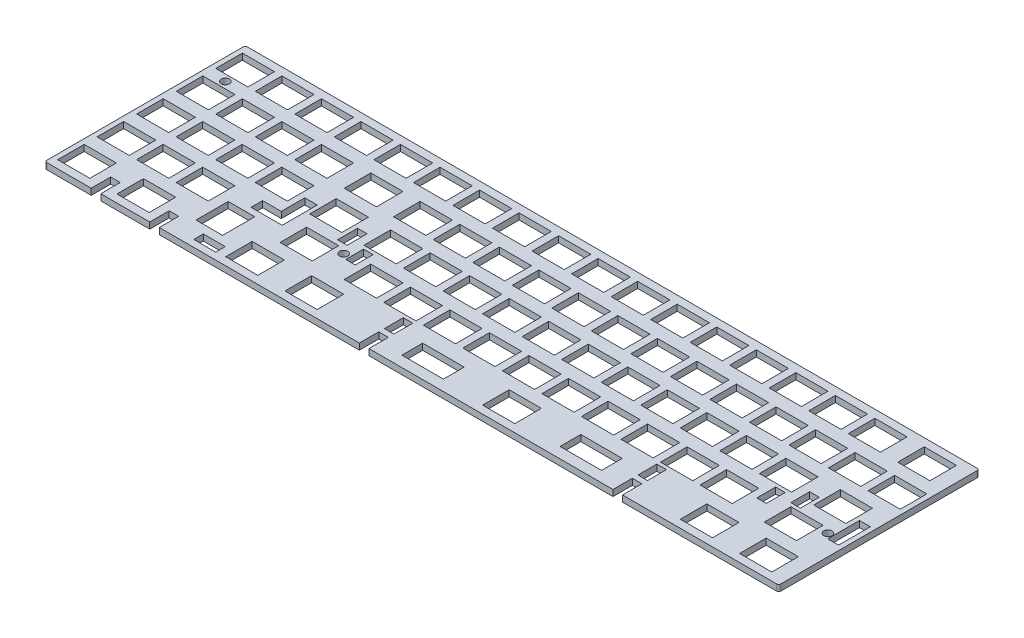
SolidWorks part; units mm, degrees
ref_plane "Front Plane" through (0, 0, 0) normal (0, 0, 1) x (1, 0, 0)
ref_plane "Top Plane" through (0, 0, 0) normal (0, 1, 0) x (1, 0, 0)
ref_plane "Right Plane" through (0, 0, 0) normal (1, 0, 0) x (0, 0, -1)
sketch "Sketch1" plane through (0, 0, 0) normal (0, 1, 0) x (1, 0, 0)
  line L0 (83.8437, 47.45) -> (83.8437, 30.525)
  line L1 (83.8437, 30.525) -> (68.8437, 30.525)
  line L2 (68.8437, 30.525) -> (68.8437, 36.125)
  line L3 (68.8437, 36.125) -> (77.8437, 36.125)
  line L4 (77.8437, 36.125) -> (77.8437, 47.45)
  line L5 (77.8437, 47.45) -> (83.8437, 47.45)
  line L6 (68.45, 7.925) -> (79.05, 7.925)
  line L7 (79.05, 7.925) -> (79.05, 3.325)
  line L8 (79.05, 3.325) -> (68.45, 3.325)
  line L9 (68.45, 3.325) -> (68.45, 7.925)
  line L10 (118.0062, 40.2) -> (113.4062, 40.2)
  line L11 (113.4062, 40.2) -> (113.4062, 31.6)
  line L12 (113.4062, 31.6) -> (118.0062, 31.6)
  line L13 (118.0062, 31.6) -> (118.0062, 40.2)
  line L14 (107.8437, 37.85) -> (107.8437, 47.45)
  line L15 (107.8437, 47.45) -> (103.2437, 47.45)
  line L16 (103.2437, 47.45) -> (103.2437, 37.85)
  line L17 (103.2437, 37.85) -> (107.8437, 37.85)
  line L18 (151.5875, 21.15) -> (156.1875, 21.15)
  line L19 (156.1875, 21.15) -> (156.1875, 12.05)
  line L20 (156.1875, 12.05) -> (151.5875, 12.05)
  line L21 (151.5875, 12.05) -> (151.5875, 21.15)
  line L22 (278.3875, 21.15) -> (273.7875, 21.15)
  line L23 (273.7875, 21.15) -> (273.7875, 12.05)
  line L24 (273.7875, 12.05) -> (278.3875, 12.05)
  line L25 (278.3875, 12.05) -> (278.3875, 21.15)
  line L26 (22.375, 0) -> (22.375, 9.35)
  line L27 (22.375, 9.35) -> (26.975, 9.35)
  line L28 (26.975, 9.35) -> (26.975, 0)
  line L29 (50.575, 0) -> (50.575, 9.35)
  line L30 (50.575, 9.35) -> (55.175, 9.35)
  line L31 (55.175, 9.35) -> (55.175, 0)
  line L32 (151.5875, 0) -> (151.5875, 9.35)
  line L33 (151.5875, 9.35) -> (156.1875, 9.35)
  line L34 (156.1875, 9.35) -> (156.1875, 0)
  line L35 (273.7875, 9.35) -> (278.3875, 9.35)
  line L36 (278.3875, 9.35) -> (278.3875, 0)
  line L37 (326.7313, 46.45) -> (322.1313, 46.45)
  line L38 (322.1313, 46.45) -> (322.1313, 37.35)
  line L39 (322.1313, 37.35) -> (326.7313, 37.35)
  line L40 (326.7313, 37.35) -> (326.7313, 46.45)
  line L41 (316.5687, 40.2) -> (311.9687, 40.2)
  line L42 (311.9687, 40.2) -> (311.9687, 31.1)
  line L43 (311.9687, 31.1) -> (316.5687, 31.1)
  line L44 (316.5687, 31.1) -> (316.5687, 40.2)
  line L45 (351.3687, 46.45) -> (346.1312, 46.45)
  line L46 (346.1312, 46.45) -> (346.1312, 31.1)
  line L47 (346.1312, 31.1) -> (351.3687, 31.1)
  line L48 (351.3687, 31.1) -> (351.3687, 46.45)
  line L49 (26.975, 0) -> (50.575, 0)
  line L50 (55.175, 0) -> (151.5875, 0)
  line L51 (156.1875, 0) -> (273.7875, 0)
  line L52 (1, 0) -> (22.375, 0)
  line L53 (278.3875, 0) -> (352.675, 0)
  line L54 (353.675, 1) -> (353.675, 95.6)
  line L55 (352.675, 96.6) -> (1, 96.6)
  line L56 (0, 1) -> (0, 95.6)
  line L57 (273.7875, 9.35) -> (273.7875, 0)
  line L58 (166.8875, 5.2) -> (186.8875, 5.2)
  line L59 (186.8875, 5.2) -> (186.8875, 15.2)
  line L60 (186.8875, 15.2) -> (166.8875, 15.2)
  line L61 (166.8875, 15.2) -> (166.8875, 5.2)
  line L62 (243.0875, 5.2) -> (263.0875, 5.2)
  line L63 (263.0875, 5.2) -> (263.0875, 15.2)
  line L64 (263.0875, 15.2) -> (243.0875, 15.2)
  line L65 (243.0875, 15.2) -> (243.0875, 5.2)
  line L66 (137.0125, 35.65) -> (121.4125, 35.65)
  line L67 (121.4125, 35.65) -> (121.4125, 22.85)
  line L68 (121.4125, 22.85) -> (137.0125, 22.85)
  line L69 (137.0125, 22.85) -> (137.0125, 35.65)
  line L70 (127.4875, 54.7) -> (111.8875, 54.7)
  line L71 (111.8875, 54.7) -> (111.8875, 41.9)
  line L72 (111.8875, 41.9) -> (127.4875, 41.9)
  line L73 (127.4875, 41.9) -> (127.4875, 54.7)
  line L74 (122.725, 73.75) -> (107.125, 73.75)
  line L75 (107.125, 73.75) -> (107.125, 60.95)
  line L76 (107.125, 60.95) -> (122.725, 60.95)
  line L77 (122.725, 60.95) -> (122.725, 73.75)
  line L78 (331.0125, 80) -> (346.5125, 80)
  line L79 (346.5125, 80) -> (346.5125, 92.8)
  line L80 (346.5125, 92.8) -> (331.0125, 92.8)
  line L81 (331.0125, 92.8) -> (331.0125, 80)
  line L82 (307.2, 80) -> (322.7, 80)
  line L83 (322.7, 80) -> (322.7, 92.8)
  line L84 (322.7, 92.8) -> (307.2, 92.8)
  line L85 (307.2, 92.8) -> (307.2, 80)
  line L86 (288.15, 80) -> (303.65, 80)
  line L87 (303.65, 80) -> (303.65, 92.8)
  line L88 (303.65, 92.8) -> (288.15, 92.8)
  line L89 (288.15, 92.8) -> (288.15, 80)
  line L90 (269.1, 80) -> (284.6, 80)
  line L91 (284.6, 80) -> (284.6, 92.8)
  line L92 (284.6, 92.8) -> (269.1, 92.8)
  line L93 (269.1, 92.8) -> (269.1, 80)
  line L94 (250.05, 80) -> (265.55, 80)
  line L95 (265.55, 80) -> (265.55, 92.8)
  line L96 (265.55, 92.8) -> (250.05, 92.8)
  line L97 (250.05, 92.8) -> (250.05, 80)
  line L98 (231, 80) -> (246.5, 80)
  line L99 (246.5, 80) -> (246.5, 92.8)
  line L100 (246.5, 92.8) -> (231, 92.8)
  line L101 (231, 92.8) -> (231, 80)
  line L102 (211.95, 80) -> (227.45, 80)
  line L103 (227.45, 80) -> (227.45, 92.8)
  line L104 (227.45, 92.8) -> (211.95, 92.8)
  line L105 (211.95, 92.8) -> (211.95, 80)
  line L106 (192.9, 80) -> (208.4, 80)
  line L107 (208.4, 80) -> (208.4, 92.8)
  line L108 (208.4, 92.8) -> (192.9, 92.8)
  line L109 (192.9, 92.8) -> (192.9, 80)
  line L110 (173.85, 80) -> (189.35, 80)
  line L111 (189.35, 80) -> (189.35, 92.8)
  line L112 (189.35, 92.8) -> (173.85, 92.8)
  line L113 (173.85, 92.8) -> (173.85, 80)
  line L114 (154.8, 80) -> (170.3, 80)
  line L115 (170.3, 80) -> (170.3, 92.8)
  line L116 (170.3, 92.8) -> (154.8, 92.8)
  line L117 (154.8, 92.8) -> (154.8, 80)
  line L118 (135.75, 80) -> (151.25, 80)
  line L119 (151.25, 80) -> (151.25, 92.8)
  line L120 (151.25, 92.8) -> (135.75, 92.8)
  line L121 (135.75, 92.8) -> (135.75, 80)
  line L122 (116.7, 80) -> (132.2, 80)
  line L123 (132.2, 80) -> (132.2, 92.8)
  line L124 (132.2, 92.8) -> (116.7, 92.8)
  line L125 (116.7, 92.8) -> (116.7, 80)
  line L126 (97.65, 80) -> (113.15, 80)
  line L127 (113.15, 80) -> (113.15, 92.8)
  line L128 (113.15, 92.8) -> (97.65, 92.8)
  line L129 (97.65, 92.8) -> (97.65, 80)
  line L130 (78.6, 80) -> (94.1, 80)
  line L131 (94.1, 80) -> (94.1, 92.8)
  line L132 (94.1, 92.8) -> (78.6, 92.8)
  line L133 (78.6, 92.8) -> (78.6, 80)
  line L134 (59.55, 80) -> (75.05, 80)
  line L135 (75.05, 80) -> (75.05, 92.8)
  line L136 (75.05, 92.8) -> (59.55, 92.8)
  line L137 (59.55, 92.8) -> (59.55, 80)
  line L138 (40.5, 80) -> (56, 80)
  line L139 (56, 80) -> (56, 92.8)
  line L140 (56, 92.8) -> (40.5, 92.8)
  line L141 (40.5, 92.8) -> (40.5, 80)
  line L142 (21.45, 80) -> (36.95, 80)
  line L143 (36.95, 80) -> (36.95, 92.8)
  line L144 (36.95, 92.8) -> (21.45, 92.8)
  line L145 (21.45, 92.8) -> (21.45, 80)
  line L146 (2.4, 80) -> (17.9, 80)
  line L147 (17.9, 80) -> (17.9, 92.8)
  line L148 (17.9, 92.8) -> (2.4, 92.8)
  line L149 (2.4, 92.8) -> (2.4, 80)
  line L150 (59.55, 60.95) -> (75.05, 60.95)
  line L151 (75.05, 60.95) -> (75.05, 73.75)
  line L152 (75.05, 73.75) -> (59.55, 73.75)
  line L153 (59.55, 73.75) -> (59.55, 60.95)
  line L154 (40.5, 60.95) -> (56, 60.95)
  line L155 (56, 60.95) -> (56, 73.75)
  line L156 (56, 73.75) -> (40.5, 73.75)
  line L157 (40.5, 73.75) -> (40.5, 60.95)
  line L158 (21.45, 60.95) -> (36.95, 60.95)
  line L159 (36.95, 60.95) -> (36.95, 73.75)
  line L160 (36.95, 73.75) -> (21.45, 73.75)
  line L161 (21.45, 73.75) -> (21.45, 60.95)
  line L162 (2.4, 60.95) -> (17.9, 60.95)
  line L163 (17.9, 60.95) -> (17.9, 73.75)
  line L164 (17.9, 73.75) -> (2.4, 73.75)
  line L165 (2.4, 73.75) -> (2.4, 60.95)
  line L166 (59.5, 41.9) -> (75, 41.9)
  line L167 (75, 41.9) -> (75, 54.7)
  line L168 (75, 54.7) -> (59.5, 54.7)
  line L169 (59.5, 54.7) -> (59.5, 41.9)
  line L170 (40.45, 41.9) -> (55.95, 41.9)
  line L171 (55.95, 41.9) -> (55.95, 54.7)
  line L172 (55.95, 54.7) -> (40.45, 54.7)
  line L173 (40.45, 54.7) -> (40.45, 41.9)
  line L174 (21.4, 41.9) -> (36.9, 41.9)
  line L175 (36.9, 41.9) -> (36.9, 54.7)
  line L176 (36.9, 54.7) -> (21.4, 54.7)
  line L177 (21.4, 54.7) -> (21.4, 41.9)
  line L178 (2.35, 41.9) -> (17.85, 41.9)
  line L179 (17.85, 41.9) -> (17.85, 54.7)
  line L180 (17.85, 54.7) -> (2.35, 54.7)
  line L181 (2.35, 54.7) -> (2.35, 41.9)
  line L182 (40.45, 22.85) -> (55.95, 22.85)
  line L183 (55.95, 22.85) -> (55.95, 35.65)
  line L184 (55.95, 35.65) -> (40.45, 35.65)
  line L185 (40.45, 35.65) -> (40.45, 22.85)
  line L186 (21.4, 22.85) -> (36.9, 22.85)
  line L187 (36.9, 22.85) -> (36.9, 35.65)
  line L188 (36.9, 35.65) -> (21.4, 35.65)
  line L189 (21.4, 35.65) -> (21.4, 22.85)
  line L190 (2.35, 22.85) -> (17.85, 22.85)
  line L191 (17.85, 22.85) -> (17.85, 35.65)
  line L192 (17.85, 35.65) -> (2.35, 35.65)
  line L193 (2.35, 35.65) -> (2.35, 22.85)
  line L194 (2.4, 3.8) -> (17.9, 3.8)
  line L195 (17.9, 3.8) -> (17.9, 16.6)
  line L196 (17.9, 16.6) -> (2.4, 16.6)
  line L197 (2.4, 16.6) -> (2.4, 3.8)
  line L198 (30.975, 3.8) -> (46.475, 3.8)
  line L199 (46.475, 3.8) -> (46.475, 16.6)
  line L200 (46.475, 16.6) -> (30.975, 16.6)
  line L201 (30.975, 16.6) -> (30.975, 3.8)
  line L202 (83.3625, 3.8) -> (98.8625, 3.8)
  line L203 (98.8625, 3.8) -> (98.8625, 16.6)
  line L204 (98.8625, 16.6) -> (83.3625, 16.6)
  line L205 (83.3625, 16.6) -> (83.3625, 3.8)
  line L206 (111.9375, 3.8) -> (127.4375, 3.8)
  line L207 (127.4375, 3.8) -> (127.4375, 16.6)
  line L208 (127.4375, 16.6) -> (111.9375, 16.6)
  line L209 (111.9375, 16.6) -> (111.9375, 3.8)
  line L210 (90.5062, 22.85) -> (106.0062, 22.85)
  line L211 (106.0062, 22.85) -> (106.0062, 35.65)
  line L212 (106.0062, 35.65) -> (90.5062, 35.65)
  line L213 (90.5062, 35.65) -> (90.5062, 22.85)
  line L214 (85.7437, 41.9) -> (101.2437, 41.9)
  line L215 (101.2437, 41.9) -> (101.2437, 54.7)
  line L216 (101.2437, 54.7) -> (85.7437, 54.7)
  line L217 (85.7437, 54.7) -> (85.7437, 41.9)
  line L218 (83.3625, 60.95) -> (98.8625, 60.95)
  line L219 (98.8625, 60.95) -> (98.8625, 73.75)
  line L220 (98.8625, 73.75) -> (83.3625, 73.75)
  line L221 (83.3625, 73.75) -> (83.3625, 60.95)
  line L222 (328.6312, 41.9) -> (344.1312, 41.9)
  line L223 (344.1312, 41.9) -> (344.1312, 54.7)
  line L224 (344.1312, 54.7) -> (328.6312, 54.7)
  line L225 (328.6312, 54.7) -> (328.6312, 41.9)
  line L226 (207.1875, 3.8) -> (222.6875, 3.8)
  line L227 (222.6875, 3.8) -> (222.6875, 16.6)
  line L228 (222.6875, 16.6) -> (207.1875, 16.6)
  line L229 (207.1875, 16.6) -> (207.1875, 3.8)
  line L230 (302.4375, 3.8) -> (317.9375, 3.8)
  line L231 (317.9375, 3.8) -> (317.9375, 16.6)
  line L232 (317.9375, 16.6) -> (302.4375, 16.6)
  line L233 (302.4375, 16.6) -> (302.4375, 3.8)
  line L234 (323.8687, 22.85) -> (339.3687, 22.85)
  line L235 (339.3687, 22.85) -> (339.3687, 35.65)
  line L236 (339.3687, 35.65) -> (323.8687, 35.65)
  line L237 (323.8687, 35.65) -> (323.8687, 22.85)
  line L238 (331.0125, 3.8) -> (346.5125, 3.8)
  line L239 (346.5125, 3.8) -> (346.5125, 16.6)
  line L240 (346.5125, 16.6) -> (331.0125, 16.6)
  line L241 (331.0125, 16.6) -> (331.0125, 3.8)
  line L242 (73.7, 11.975) -> (73.7, 27.475)
  line L243 (73.7, 27.475) -> (60.9, 27.475)
  line L244 (60.9, 27.475) -> (60.9, 11.975)
  line L245 (60.9, 11.975) -> (73.7, 11.975)
  line L246 (278.625, 60.95) -> (294.125, 60.95)
  line L247 (294.125, 60.95) -> (294.125, 73.75)
  line L248 (294.125, 73.75) -> (278.625, 73.75)
  line L249 (278.625, 73.75) -> (278.625, 60.95)
  line L250 (259.575, 60.95) -> (275.075, 60.95)
  line L251 (275.075, 60.95) -> (275.075, 73.75)
  line L252 (275.075, 73.75) -> (259.575, 73.75)
  line L253 (259.575, 73.75) -> (259.575, 60.95)
  line L254 (240.525, 60.95) -> (256.025, 60.95)
  line L255 (256.025, 60.95) -> (256.025, 73.75)
  line L256 (256.025, 73.75) -> (240.525, 73.75)
  line L257 (240.525, 73.75) -> (240.525, 60.95)
  line L258 (221.475, 60.95) -> (236.975, 60.95)
  line L259 (236.975, 60.95) -> (236.975, 73.75)
  line L260 (236.975, 73.75) -> (221.475, 73.75)
  line L261 (221.475, 73.75) -> (221.475, 60.95)
  line L262 (202.425, 60.95) -> (217.925, 60.95)
  line L263 (217.925, 60.95) -> (217.925, 73.75)
  line L264 (217.925, 73.75) -> (202.425, 73.75)
  line L265 (202.425, 73.75) -> (202.425, 60.95)
  line L266 (183.375, 60.95) -> (198.875, 60.95)
  line L267 (198.875, 60.95) -> (198.875, 73.75)
  line L268 (198.875, 73.75) -> (183.375, 73.75)
  line L269 (183.375, 73.75) -> (183.375, 60.95)
  line L270 (164.325, 60.95) -> (179.825, 60.95)
  line L271 (179.825, 60.95) -> (179.825, 73.75)
  line L272 (179.825, 73.75) -> (164.325, 73.75)
  line L273 (164.325, 73.75) -> (164.325, 60.95)
  line L274 (145.275, 60.95) -> (160.775, 60.95)
  line L275 (160.775, 60.95) -> (160.775, 73.75)
  line L276 (160.775, 73.75) -> (145.275, 73.75)
  line L277 (145.275, 73.75) -> (145.275, 60.95)
  line L278 (126.225, 60.95) -> (141.725, 60.95)
  line L279 (141.725, 60.95) -> (141.725, 73.75)
  line L280 (141.725, 73.75) -> (126.225, 73.75)
  line L281 (126.225, 73.75) -> (126.225, 60.95)
  line L282 (283.3875, 41.9) -> (298.8875, 41.9)
  line L283 (298.8875, 41.9) -> (298.8875, 54.7)
  line L284 (298.8875, 54.7) -> (283.3875, 54.7)
  line L285 (283.3875, 54.7) -> (283.3875, 41.9)
  line L286 (264.3375, 41.9) -> (279.8375, 41.9)
  line L287 (279.8375, 41.9) -> (279.8375, 54.7)
  line L288 (279.8375, 54.7) -> (264.3375, 54.7)
  line L289 (264.3375, 54.7) -> (264.3375, 41.9)
  line L290 (245.2875, 41.9) -> (260.7875, 41.9)
  line L291 (260.7875, 41.9) -> (260.7875, 54.7)
  line L292 (260.7875, 54.7) -> (245.2875, 54.7)
  line L293 (245.2875, 54.7) -> (245.2875, 41.9)
  line L294 (226.2375, 41.9) -> (241.7375, 41.9)
  line L295 (241.7375, 41.9) -> (241.7375, 54.7)
  line L296 (241.7375, 54.7) -> (226.2375, 54.7)
  line L297 (226.2375, 54.7) -> (226.2375, 41.9)
  line L298 (207.1875, 41.9) -> (222.6875, 41.9)
  line L299 (222.6875, 41.9) -> (222.6875, 54.7)
  line L300 (222.6875, 54.7) -> (207.1875, 54.7)
  line L301 (207.1875, 54.7) -> (207.1875, 41.9)
  line L302 (188.1375, 41.9) -> (203.6375, 41.9)
  line L303 (203.6375, 41.9) -> (203.6375, 54.7)
  line L304 (203.6375, 54.7) -> (188.1375, 54.7)
  line L305 (188.1375, 54.7) -> (188.1375, 41.9)
  line L306 (169.0875, 41.9) -> (184.5875, 41.9)
  line L307 (184.5875, 41.9) -> (184.5875, 54.7)
  line L308 (184.5875, 54.7) -> (169.0875, 54.7)
  line L309 (169.0875, 54.7) -> (169.0875, 41.9)
  line L310 (150.0375, 41.9) -> (165.5375, 41.9)
  line L311 (165.5375, 41.9) -> (165.5375, 54.7)
  line L312 (165.5375, 54.7) -> (150.0375, 54.7)
  line L313 (150.0375, 54.7) -> (150.0375, 41.9)
  line L314 (130.9875, 41.9) -> (146.4875, 41.9)
  line L315 (146.4875, 41.9) -> (146.4875, 54.7)
  line L316 (146.4875, 54.7) -> (130.9875, 54.7)
  line L317 (130.9875, 54.7) -> (130.9875, 41.9)
  line L318 (292.9125, 22.85) -> (308.4125, 22.85)
  line L319 (308.4125, 22.85) -> (308.4125, 35.65)
  line L320 (308.4125, 35.65) -> (292.9125, 35.65)
  line L321 (292.9125, 35.65) -> (292.9125, 22.85)
  line L322 (273.8625, 22.85) -> (289.3625, 22.85)
  line L323 (289.3625, 22.85) -> (289.3625, 35.65)
  line L324 (289.3625, 35.65) -> (273.8625, 35.65)
  line L325 (273.8625, 35.65) -> (273.8625, 22.85)
  line L326 (254.8125, 22.85) -> (270.3125, 22.85)
  line L327 (270.3125, 22.85) -> (270.3125, 35.65)
  line L328 (270.3125, 35.65) -> (254.8125, 35.65)
  line L329 (254.8125, 35.65) -> (254.8125, 22.85)
  line L330 (235.7625, 22.85) -> (251.2625, 22.85)
  line L331 (251.2625, 22.85) -> (251.2625, 35.65)
  line L332 (251.2625, 35.65) -> (235.7625, 35.65)
  line L333 (235.7625, 35.65) -> (235.7625, 22.85)
  line L334 (216.7125, 22.85) -> (232.2125, 22.85)
  line L335 (232.2125, 22.85) -> (232.2125, 35.65)
  line L336 (232.2125, 35.65) -> (216.7125, 35.65)
  line L337 (216.7125, 35.65) -> (216.7125, 22.85)
  line L338 (197.6625, 22.85) -> (213.1625, 22.85)
  line L339 (213.1625, 22.85) -> (213.1625, 35.65)
  line L340 (213.1625, 35.65) -> (197.6625, 35.65)
  line L341 (197.6625, 35.65) -> (197.6625, 22.85)
  line L342 (178.6125, 22.85) -> (194.1125, 22.85)
  line L343 (194.1125, 22.85) -> (194.1125, 35.65)
  line L344 (194.1125, 35.65) -> (178.6125, 35.65)
  line L345 (178.6125, 35.65) -> (178.6125, 22.85)
  line L346 (159.5625, 22.85) -> (175.0625, 22.85)
  line L347 (175.0625, 22.85) -> (175.0625, 35.65)
  line L348 (175.0625, 35.65) -> (159.5625, 35.65)
  line L349 (159.5625, 35.65) -> (159.5625, 22.85)
  line L350 (140.5125, 22.85) -> (156.0125, 22.85)
  line L351 (156.0125, 22.85) -> (156.0125, 35.65)
  line L352 (156.0125, 35.65) -> (140.5125, 35.65)
  line L353 (140.5125, 35.65) -> (140.5125, 22.85)
  line L354 (335.775, 60.95) -> (351.275, 60.95)
  line L355 (351.275, 60.95) -> (351.275, 73.75)
  line L356 (351.275, 73.75) -> (335.775, 73.75)
  line L357 (335.775, 73.75) -> (335.775, 60.95)
  line L358 (316.725, 60.95) -> (332.225, 60.95)
  line L359 (332.225, 60.95) -> (332.225, 73.75)
  line L360 (332.225, 73.75) -> (316.725, 73.75)
  line L361 (316.725, 73.75) -> (316.725, 60.95)
  line L362 (297.675, 60.95) -> (313.175, 60.95)
  line L363 (313.175, 60.95) -> (313.175, 73.75)
  line L364 (313.175, 73.75) -> (297.675, 73.75)
  line L365 (297.675, 73.75) -> (297.675, 60.95)
  line L366 (302.4375, 41.9) -> (317.9375, 41.9)
  line L367 (317.9375, 41.9) -> (317.9375, 54.7)
  line L368 (317.9375, 54.7) -> (302.4375, 54.7)
  line L369 (302.4375, 54.7) -> (302.4375, 41.9)
  arc A0 (0, 1) -> (1, 0) centre (1, 1) ccw
  arc A1 (353.675, 95.6) -> (352.675, 96.6) centre (352.675, 95.6) ccw
  arc A2 (352.675, 0) -> (353.675, 1) centre (352.675, 1) ccw
  arc A3 (1, 96.6) -> (0, 95.6) centre (1, 95.6) ccw
  circle A4 centre (343.8687, 33.5) radius 2
  circle A5 centre (110.5062, 33.5) radius 2
  circle A6 centre (10.15, 76.875) radius 2
extrude "Boss-Extrude1" add sketch "Sketch1" against normal blind 3
